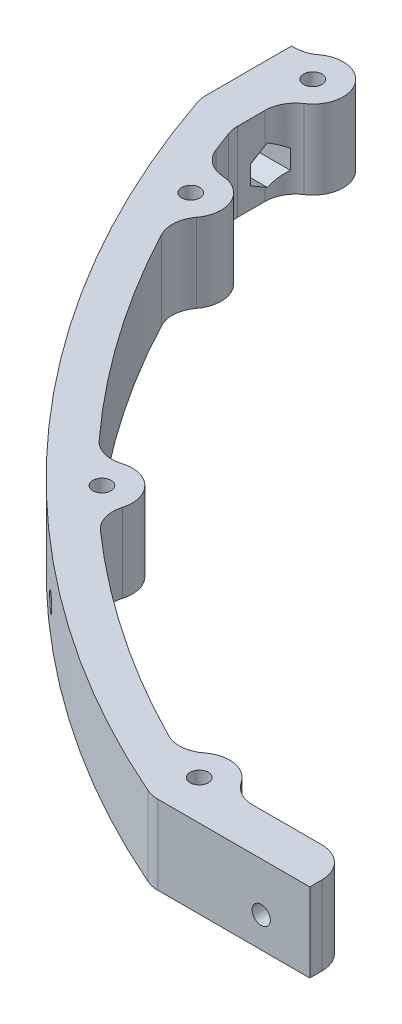
SolidWorks part; units mm, degrees
material "ABS"
ref_plane "Plan de face" through (0, 0, 0) normal (0, 0, 1) x (1, 0, 0)
ref_plane "Plan de dessus" through (0, 0, 0) normal (0, 1, 0) x (1, 0, 0)
ref_plane "Plan de droite" through (0, 0, 0) normal (1, 0, 0) x (0, 0, -1)
sketch "Esquisse1" plane through (0, 0, 0) normal (0, 1, 0) x (1, 0, 0)
  line L1 (0, 49) -> (165, 49)
  line L2 (0, 49) -> (0, -160)
  line L3 (0, -160) -> (68.3813, -160)
  line L4 (165, 49) -> (165, -55.2359)
  arc A0 (68.3813, -160) -> (165, -55.2359) centre (0, 0) ccw
  dimension "D4" = 348
  dimension "D1" = 49
  dimension "D2" = 165
  dimension "D3" = 160
extrude "Boss.-Extru.1" add sketch "Esquisse1" along normal blind 8 and the other way blind 5
mirror "Symétrie1" about plane through (0, -5, -49) normal (-1, 0, 0) of bodies 101 102
sketch "Esquisse7" plane through (0, 8, 0) normal (0, 1, 0) x (1, 0, 0)
  line L0 (-68.3813, -160) -> (68.3813, -160) construction
  line L1 (-165, -55.2359) -> (-165, 49) construction
  line L2 (165, -55.2359) -> (165, 49) construction
  line L3 (0, -7.15) -> (0, 7.15) construction
  line L4 (165, 49) -> (-165, 49) construction
  circle A0 centre (-157, -43) radius 1.5
  circle A1 centre (157, -43) radius 1.5
  circle A5 centre (157, 43) radius 1.5
  circle A13 centre (-157, 43) radius 1.5
  circle A14 centre (-114, 43) radius 1.5
  circle A15 centre (-90, 43) radius 1.5
  circle A16 centre (90, 43) radius 1.5
  circle A17 centre (114, 43) radius 1.5
  dimension "D5" = 3
  dimension "D3" = 43
  dimension "D4" = 86
  dimension "D8" = 117
  dimension "D9" = 8
  dimension "D6" = 8
  dimension "D7" = 24
  dimension "D10" = 180
  dimension "D11" = 6
  dimension "D12" = 90
  dimension "D13" = 114
  dimension "D1" = 2
  dimension "D2" = 2
extrude "Enlèv. mat.-Extru.5" cut sketch "Esquisse7" against normal through all
sketch "Esquisse11" plane through (0, 8, 0) normal (0, 1, 0) x (1, 0, 0)
  line L0 (0, -7.15) -> (0, 7.15) construction
  line L1 (-68.3813, -160) -> (68.3813, -160) construction
  circle A0 centre (-150.8698, -69.241) radius 1.5
  circle A1 centre (-116.4, -118.3514) radius 1.5
  circle A2 centre (-66.7233, -152) radius 1.5
  circle A3 centre (66.7233, -152) radius 1.5
  circle A4 centre (116.4, -118.3514) radius 1.5
  circle A5 centre (150.8698, -69.241) radius 1.5
  circle A6 centre (-15, -152) radius 1.5
  circle A7 centre (0, 0) radius 166 construction
  arc A8 (-165, -55.2359) -> (-68.3813, -160) centre (0, 0) ccw construction
  circle A9 centre (15, -152) radius 1.5
  dimension "D1" = 8
  dimension "D2" = 8
  dimension "D3" = 3
  dimension "D4" = 60
  dimension "D5" = 60
  dimension "D6" = 51.7233
  dimension "D7" = 30
extrude "Enlèv. mat.-Extru.9" cut sketch "Esquisse11" against normal through all
sketch "Esquisse12" plane through (0, 8, 0) normal (0, 1, 0) x (1, 0, 0)
  line L3 (163.5, 47.5) -> (-163.5, 47.5)
  line L4 (-163.5, 47.5) -> (-163.5, -54.9909)
  line L5 (-68.0735, -158.5) -> (68.0735, -158.5)
  line L6 (163.5, -54.9909) -> (163.5, 47.5)
  line L7 (165, 49) -> (-165, 49)
  line L8 (-165, 49) -> (-165, -55.2359)
  line L9 (-68.3813, -160) -> (68.3813, -160)
  line L10 (165, -55.2359) -> (165, 49)
  line L11 (165, 49) -> (-165, 49)
  line L12 (-165, 49) -> (-165, -55.2359)
  line L13 (-68.3813, -160) -> (68.3813, -160)
  line L14 (165, -55.2359) -> (165, 49)
  arc A0 (-163.5, -54.9909) -> (-68.0735, -158.5) centre (0, 0) ccw
  arc A1 (68.0735, -158.5) -> (163.5, -54.9909) centre (0, 0) ccw
  arc A2 (-165, -55.2359) -> (-68.3813, -160) centre (0, 0) ccw
  arc A3 (68.3813, -160) -> (165, -55.2359) centre (0, 0) ccw
  arc A4 (-165, -55.2359) -> (-68.3813, -160) centre (0, 0) ccw
  arc A5 (68.3813, -160) -> (165, -55.2359) centre (0, 0) ccw
  dimension "D1" = 0
  dimension "D2" = 1.5
extrude "Enlèv. mat.-Extru.10" cut sketch "Esquisse12" against normal through all
sketch "Esquisse13" plane through (0, 8, 0) normal (0, 1, 0) x (1, 0, 0)
  line L0 (163.5, -54.9909) -> (163.5, 47.5) construction
  line L1 (-163.5, 47.5) -> (163.5, 47.5)
  line L2 (-163.5, 47.5) -> (-163.5, -40)
  line L3 (-163.5, -40) -> (-156.5, -40)
  line L4 (163.5, 47.5) -> (163.5, -158.5)
  line L5 (-69.0652, -151.5) -> (-42, -151.5)
  line L6 (-42, -151.5) -> (-42, -158.5)
  line L7 (-68.0735, -158.5) -> (68.0735, -158.5) construction
  line L8 (-42, -158.5) -> (163.5, -158.5)
  line L9 (-156.5, -40) -> (-156.5, -56.8331)
  arc A0 (-156.5, -56.8331) -> (-69.0652, -151.5) centre (0, 0) ccw
  arc A1 (-163.5, -54.9909) -> (-68.0735, -158.5) centre (0, 0) ccw construction
  dimension "D1" = 7
  dimension "D2" = 6
  dimension "D3" = 42
  dimension "D4" = 7
  dimension "D5" = 40
extrude "Enlèv. mat.-Extru.11" cut sketch "Esquisse13" against normal through all
sketch "Esquisse14" plane through (0, 8, 0) normal (0, 1, 0) x (1, 0, 0)
  circle A0 centre (-157, -43) radius 5
  circle A1 centre (-157, -43) radius 1.5
  circle A2 centre (-150.8698, -69.241) radius 1.5
  circle A3 centre (-150.8698, -69.241) radius 5
  circle A4 centre (-116.4, -118.3514) radius 1.5
  circle A5 centre (-116.4, -118.3514) radius 5
  circle A6 centre (-66.7233, -152) radius 5
  circle A7 centre (-66.7233, -152) radius 1.5
  arc A8 (-156.5, -41.5858) -> (-156.5, -44.4142) centre (-157, -43) ccw construction
  arc A9 (-151.9095, -68.1598) -> (-150.728, -70.7342) centre (-150.8698, -69.241) ccw construction
  arc A10 (-117.7561, -117.7104) -> (-115.7366, -119.6967) centre (-116.4, -118.3514) ccw construction
  dimension "D1" = 10
extrude "Boss.-Extru.2" add sketch "Esquisse14" against normal up to surface (13 mm away) up to face at (-116.3673, -5, 99.6192)
fillet "Congé1" radius 5 12 edges at (-120.2502, 1.5, 115.1614) (-113.1464, 1.5, 122.148) (-149.1784, 1.5, 73.9462) (-153.3345, 1.5, 64.8906) (-156.5, 1.5, 56.8331) (-156.5, 1.5, 47.9749) (-163.5, 1.5, 54.9909) (-68.0735, 1.5, 158.5) (-61.7484, 1.5, 151.5) (-71.456, 1.5, 150.3871) (-42, 1.5, 151.5) (-161, 1.5, 40)
sketch "Esquisse15" plane through (0, 0, 0) normal (1, 0, 0) x (0, 0, -1)
  circle A0 centre (-51, 0) radius 1.5
  dimension "D1" = 51
  dimension "D2" = 3
extrude "Enlèv. mat.-Extru.12" cut sketch "Esquisse15" against normal through all
sketch "Esquisse16" plane through (0, 0, 0) normal (0, 0, 1) x (1, 0, 0)
  circle A0 centre (-50, 0) radius 1.5
  dimension "D1" = 3
  dimension "D2" = 50
extrude "Enlèv. mat.-Extru.13" cut sketch "Esquisse16" along normal through all
ref_plane "Plan1" through (-160.497, 0, 63.2215) normal (-0.9304, 0, 0.3665) x (0, 1, 0)
sketch "Esquisse17" plane through (-160.497, 0, 63.2215) normal (-0.9304, 0, 0.3665) x (0, 1, 0)
  circle A0 centre (0, 0) radius 1.5
  dimension "D1" = 3
extrude "Enlèv. mat.-Extru.14" cut sketch "Esquisse17" against normal through all
sketch "Esquisse18" plane through (-160.497, 0, 63.2215) normal (-0.9304, 0, 0.3665) x (0, 1, 0)
  line L1 (3.1754, 0) -> (1.5877, 2.75)
  line L2 (1.5877, 2.75) -> (-1.5877, 2.75)
  line L3 (-1.5877, 2.75) -> (-3.1754, 0)
  line L4 (-3.1754, 0) -> (-1.5877, -2.75)
  line L5 (-1.5877, -2.75) -> (1.5877, -2.75)
  line L6 (1.5877, -2.75) -> (3.1754, 0)
  circle A0 centre (0, 0) radius 2.75 construction
  dimension "D1" = 5.5
extrude "Enlèv. mat.-Extru.15" cut sketch "Esquisse18" against normal through all from offset 3 offset against normal yes
pattern_circular "Répétition circulaire1" count 3 every 28 about axis through (0, 0, 0) along (0, 1, 0) of "Enlèv. mat.-Extru.14", "Enlèv. mat.-Extru.15"
sketch "Esquisse19" plane through (0, 0, 158.5) normal (0, 0, 1) x (1, 0, 0)
  line L1 (-47.25, -1.5877) -> (-47.25, 1.5877)
  line L2 (-47.25, 1.5877) -> (-50, 3.1754)
  line L3 (-50, 3.1754) -> (-52.75, 1.5877)
  line L4 (-52.75, 1.5877) -> (-52.75, -1.5877)
  line L5 (-52.75, -1.5877) -> (-50, -3.1754)
  line L6 (-50, -3.1754) -> (-47.25, -1.5877)
  circle A0 centre (-50, 0) radius 2.75 construction
  dimension "D1" = 5.5
extrude "Enlèv. mat.-Extru.16" cut sketch "Esquisse19" against normal through all from offset 3 offset against normal yes
sketch "Esquisse20" plane through (0, -5, 0) normal (0, -1, 0) x (1, 0, 0)
  line L1 (-63.9733, 153.5877) -> (-66.7233, 155.1754)
  line L2 (-66.7233, 155.1754) -> (-69.4733, 153.5877)
  line L3 (-69.4733, 153.5877) -> (-69.4733, 150.4123)
  line L4 (-69.4733, 150.4123) -> (-66.7233, 148.8246)
  line L5 (-66.7233, 148.8246) -> (-63.9733, 150.4123)
  line L6 (-63.9733, 150.4123) -> (-63.9733, 153.5877)
  line L7 (-115.6035, 121.4253) -> (-118.6638, 120.5781)
  line L8 (-118.6638, 120.5781) -> (-119.4603, 117.5042)
  line L9 (-119.4603, 117.5042) -> (-117.1965, 115.2775)
  line L10 (-117.1965, 115.2775) -> (-114.1361, 116.1246)
  line L11 (-114.1361, 116.1246) -> (-113.3396, 119.1985)
  line L12 (-113.3396, 119.1985) -> (-115.6035, 121.4253)
  line L13 (-151.218, 72.3972) -> (-153.7773, 70.5175)
  line L14 (-153.7773, 70.5175) -> (-153.429, 67.3612)
  line L15 (-153.429, 67.3612) -> (-150.5215, 66.0847)
  line L16 (-150.5215, 66.0847) -> (-147.9622, 67.9644)
  line L17 (-147.9622, 67.9644) -> (-148.3105, 71.1207)
  line L18 (-148.3105, 71.1207) -> (-151.218, 72.3972)
  line L19 (-158.5877, 40.25) -> (-155.4123, 40.25)
  line L20 (-155.4123, 40.25) -> (-153.8246, 43)
  line L21 (-153.8246, 43) -> (-155.4123, 45.75)
  line L22 (-155.4123, 45.75) -> (-158.5877, 45.75)
  line L23 (-158.5877, 45.75) -> (-160.1754, 43)
  line L24 (-160.1754, 43) -> (-158.5877, 40.25)
  circle A0 centre (-66.7233, 152) radius 2.75 construction
  circle A1 centre (-116.4, 118.3514) radius 2.75 construction
  circle A2 centre (-150.8698, 69.241) radius 2.75 construction
  circle A3 centre (-157, 43) radius 2.75 construction
  dimension "D1" = 5.5
extrude "Enlèv. mat.-Extru.17" cut sketch "Esquisse20" against normal offset from surface (10 mm away) 3
sketch "Esquisse23" plane through (-163.5, 0, 0) normal (-1, 0, 0) x (0, 0, 1)
  line L1 (53.75, 1.5877) -> (51, 3.1754)
  line L2 (51, 3.1754) -> (48.25, 1.5877)
  line L3 (48.25, 1.5877) -> (48.25, -1.5877)
  line L4 (48.25, -1.5877) -> (51, -3.1754)
  line L5 (51, -3.1754) -> (53.75, -1.5877)
  line L6 (53.75, -1.5877) -> (53.75, 1.5877)
  circle A0 centre (51, 0) radius 2.75 construction
  circle A1 centre (51, 0) radius 1.5 construction
  dimension "D1" = 5.5
extrude "Enlèv. mat.-Extru.20" cut sketch "Esquisse23" against normal through all from offset 3 offset against normal yes
sketch "Esquisse24" plane through (0, 8, 0) normal (0, 1, 0) x (1, 0, 0)
  line L6 (-163.5, -40) -> (-163.5, -54.1664)
  line L7 (-67.0373, -158.5) -> (-42, -158.5)
  line L8 (-42, -158.5) -> (-42, -156.5)
  line L9 (-47, -151.5) -> (-58.3717, -151.5)
  line L10 (-156.5, -55.9464) -> (-156.5, -51.3516)
  line L11 (-163, -40) -> (-163.5, -40)
  line L12 (-163.5, -40) -> (-163.5, -54.1664)
  line L13 (-67.0373, -158.5) -> (-42, -158.5)
  line L14 (-42, -158.5) -> (-42, -156.5)
  line L15 (-47, -151.5) -> (-58.3717, -151.5)
  line L16 (-156.5, -55.9464) -> (-156.5, -51.3516)
  line L17 (-163, -40) -> (-163.5, -40)
  arc A20 (-163.5, -54.1664) -> (-163.2313, -55.7833) centre (-158.5, -54.1664) ccw
  arc A21 (-163.2313, -55.7833) -> (-69.0384, -158.0821) centre (0, 0) ccw
  arc A22 (-69.0384, -158.0821) -> (-67.0373, -158.5) centre (-67.0373, -153.5) ccw
  arc A23 (-42, -156.5) -> (-47, -151.5) centre (-47, -156.5) ccw
  arc A24 (-62.5475, -149.25) -> (-58.3717, -151.5) centre (-58.3717, -146.5) ccw
  arc A25 (-62.5475, -149.25) -> (-69.8019, -148.0602) centre (-66.7233, -152) ccw
  arc A26 (-75.1369, -148.5823) -> (-69.8019, -148.0602) centre (-72.8805, -144.1204) ccw
  arc A27 (-110.1048, -124.8966) -> (-75.1369, -148.5823) centre (0, 0) ccw
  arc A28 (-111.5992, -119.7487) -> (-110.1048, -124.8966) centre (-106.7984, -121.146) ccw
  arc A29 (-111.5992, -119.7487) -> (-117.8769, -113.5745) centre (-116.4, -118.3514) ccw
  arc A30 (-123.049, -112.1659) -> (-117.8769, -113.5745) centre (-119.3538, -108.7976) ccw
  arc A31 (-147.3127, -77.5966) -> (-123.049, -112.1659) centre (0, 0) ccw
  arc A32 (-146.8793, -72.2537) -> (-147.3127, -77.5966) centre (-142.8889, -75.2663) ccw
  arc A33 (-146.8793, -72.2537) -> (-150.5521, -64.2511) centre (-150.8698, -69.241) ccw
  arc A34 (-154.8856, -61.0959) -> (-150.5521, -64.2511) centre (-150.2344, -59.2612) ccw
  arc A35 (-156.1904, -57.6785) -> (-154.8856, -61.0959) centre (0, 0) ccw
  arc A36 (-156.5, -55.9464) -> (-156.1904, -57.6785) centre (-151.5, -55.9464) ccw
  arc A37 (-154.25, -47.1758) -> (-156.5, -51.3516) centre (-151.5, -51.3516) ccw
  arc A38 (-154.25, -47.1758) -> (-160, -39) centre (-157, -43) ccw
  arc A39 (-163, -40) -> (-160, -39) centre (-163, -35) ccw
  arc A40 (-163.5, -54.1664) -> (-163.2313, -55.7833) centre (-158.5, -54.1664) ccw
  arc A41 (-163.2313, -55.7833) -> (-69.0384, -158.0821) centre (0, 0) ccw
  arc A42 (-69.0384, -158.0821) -> (-67.0373, -158.5) centre (-67.0373, -153.5) ccw
  arc A43 (-42, -156.5) -> (-47, -151.5) centre (-47, -156.5) ccw
  arc A44 (-62.5475, -149.25) -> (-58.3717, -151.5) centre (-58.3717, -146.5) ccw
  arc A45 (-62.5475, -149.25) -> (-69.8019, -148.0602) centre (-66.7233, -152) ccw
  arc A46 (-75.1369, -148.5823) -> (-69.8019, -148.0602) centre (-72.8805, -144.1204) ccw
  arc A47 (-110.1048, -124.8966) -> (-75.1369, -148.5823) centre (0, 0) ccw
  arc A48 (-111.5992, -119.7487) -> (-110.1048, -124.8966) centre (-106.7984, -121.146) ccw
  arc A49 (-111.5992, -119.7487) -> (-117.8769, -113.5745) centre (-116.4, -118.3514) ccw
  arc A50 (-123.049, -112.1659) -> (-117.8769, -113.5745) centre (-119.3538, -108.7976) ccw
  arc A51 (-147.3127, -77.5966) -> (-123.049, -112.1659) centre (0, 0) ccw
  arc A52 (-146.8793, -72.2537) -> (-147.3127, -77.5966) centre (-142.8889, -75.2663) ccw
  arc A53 (-146.8793, -72.2537) -> (-150.5521, -64.2511) centre (-150.8698, -69.241) ccw
  arc A54 (-154.8856, -61.0959) -> (-150.5521, -64.2511) centre (-150.2344, -59.2612) ccw
  arc A55 (-156.1904, -57.6785) -> (-154.8856, -61.0959) centre (0, 0) ccw
  arc A56 (-156.5, -55.9464) -> (-156.1904, -57.6785) centre (-151.5, -55.9464) ccw
  arc A57 (-154.25, -47.1758) -> (-156.5, -51.3516) centre (-151.5, -51.3516) ccw
  arc A58 (-154.25, -47.1758) -> (-160, -39) centre (-157, -43) ccw
  arc A59 (-163, -40) -> (-160, -39) centre (-163, -35) ccw
  dimension "D1" = 0
extrude "Boss.-Extru.3" [suppressed] add sketch "Esquisse24" against normal blind 0.2
equation "\"D3@Esquisse7\"=\"D4@Esquisse7\"*(\"D2@Esquisse7\"-1)/2"
equation "\"D6@Esquisse7\"=\"D9@Esquisse7\""
